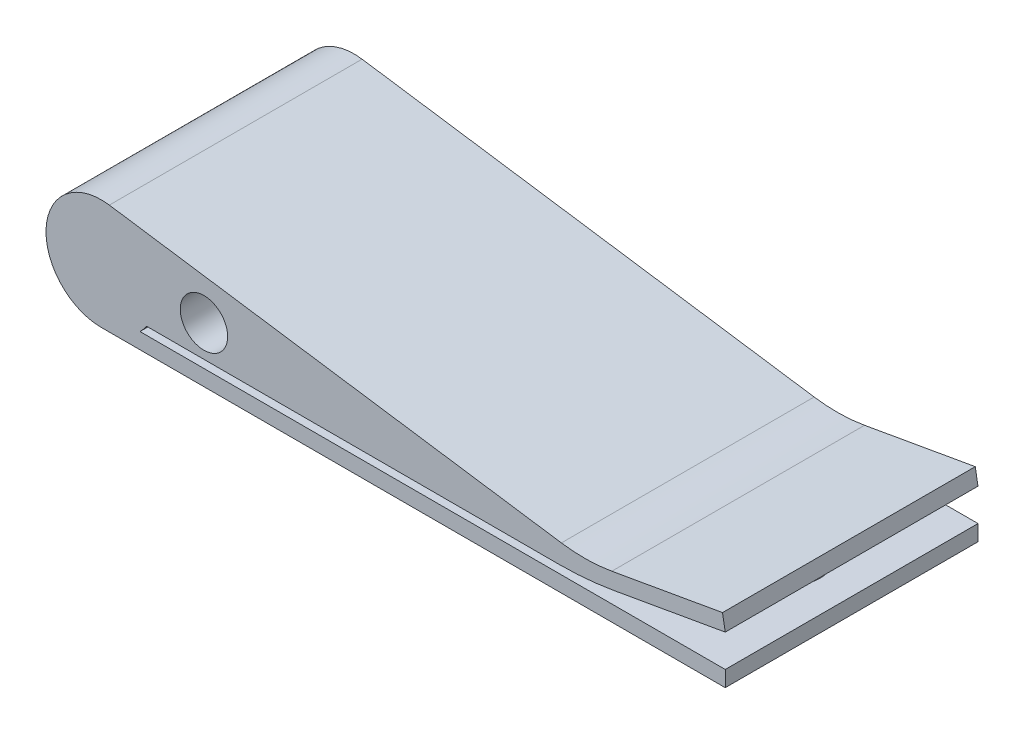
SolidWorks part; units mm, degrees
material "Acciaio inossidabile fuso"
ref_plane "Piano frontale" through (0, 0, 0) normal (0, 0, 1) x (1, 0, 0)
ref_plane "Piano superiore" through (0, 0, 0) normal (0, 1, 0) x (1, 0, 0)
ref_plane "Piano destro" through (0, 0, 0) normal (1, 0, 0) x (0, 0, -1)
sketch "Schizzo1" plane through (0, 0, 0) normal (0, 0, 1) x (1, 0, 0)
  line L0 (3.5, 0) -> (43, 0)
  line L1 (43, 0) -> (43, 1)
  line L2 (43, 1) -> (5.9495, 1)
  line L4 (6.3723, 1.5) -> (34.2264, 1.5)
  line L5 (34.2264, 1.5) -> (43, 3.047)
  line L6 (43, 3.047) -> (42.8264, 4.0318)
  line L9 (42.8264, 4.0318) -> (34.2264, 2.5154)
  line L10 (34.2264, 2.5154) -> (4.0096, 6.9627)
  line L12 (43, 1) -> (43, 3.047) construction
  line L13 (34.2264, 2.5154) -> (34.2264, 1.5) construction
  arc A0 (5.9495, 1) -> (6.3723, 1.5) centre (3.5, 3.5) ccw
  arc A1 (4.0096, 6.9627) -> (3.5, 0) centre (3.5, 3.5) ccw
  dimension "D1" = 7
  dimension "D2" = 43
  dimension "D3" = 1
  dimension "D4" = 0.5
  dimension "D5" = 80
  dimension "D6" = 8.6
  dimension "D7" = 3.5
extrude "Estrusione-Estrusione1" add sketch "Schizzo1" along normal blind 16 contours L2 A0 L4 L5 L6 L9 L10 A1 L0 L1
fillet "Raccordo1" radius 10 1 edges at (34.2264, 2.5154, 8)
fillet "Raccordo2" radius 20 1 edges at (34.2264, 1.5, 8)
sketch "Schizzo3" plane through (0, 0, 16) normal (0, 0, 1) x (1, 0, 0)
  circle A0 centre (10, 3.5) radius 1.5
  dimension "D1" = 3
  dimension "D2" = 10
  dimension "D3" = 3.5
extrude "Taglio-Estrusione1" cut sketch "Schizzo3" against normal blind 16
sketch "Schizzo4" plane through (0, 0, 0) normal (0, -1, 0) x (1, 0, 0)
  line L0 (43, 16) -> (43, 0) construction
  line L1 (16, 8) -> (39, 8) construction
  line L2 (3.5, 0) -> (43, 0) construction
  circle A0 centre (39, 8) radius 2
  circle A1 centre (16, 8) radius 2
  dimension "D2" = 4
  dimension "D1" = 4
  dimension "D3" = 8
  dimension "D4" = 23
extrude "Taglio-Estrusione2" cut sketch "Schizzo4" against normal blind 1
